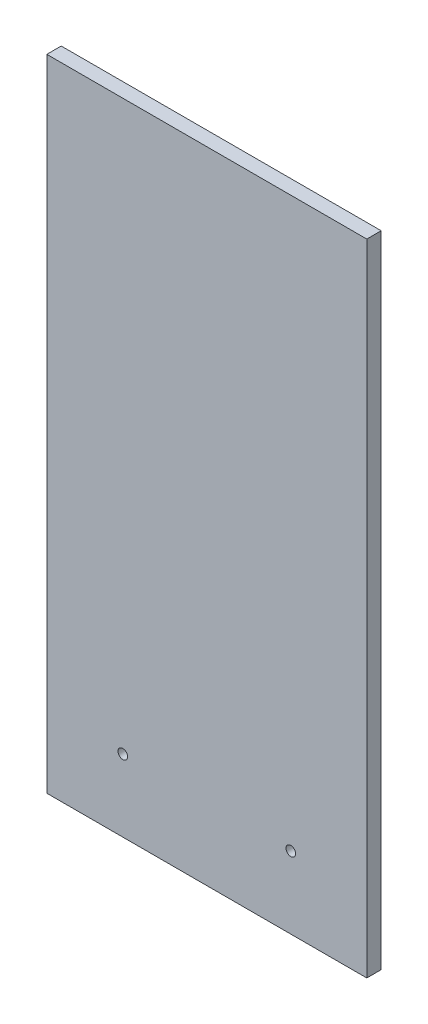
SolidWorks part; units mm, degrees
ref_plane "Plan de face" through (0, 0, 0) normal (0, 0, 1) x (1, 0, 0)
ref_plane "Plan de dessus" through (0, 0, 0) normal (0, 1, 0) x (1, 0, 0)
ref_plane "Plan de droite" through (0, 0, 0) normal (1, 0, 0) x (0, 0, -1)
sketch "Esquisse1" plane through (0, 0, 0) normal (0, 0, 1) x (1, 0, 0)
  line L1 (0, 0) -> (400, 0)
  line L2 (0, 0) -> (0, 800)
  line L3 (0, 800) -> (400, 800)
  line L4 (400, 0) -> (400, 800)
  dimension "D1" = 400
  dimension "D2" = 800
extrude "Boss.-Extru.1" add sketch "Esquisse1" along normal blind 18
sketch "Esquisse2" plane through (0, 0, 18) normal (0, 0, 1) x (1, 0, 0)
  line L0 (200, 0) -> (200, 90) construction
  line L1 (0, 0) -> (400, 0) construction
  line L2 (200, 90) -> (95, 90) construction
  circle A0 centre (95, 90) radius 6
  circle A1 centre (305, 90) radius 6
  dimension "D1" = 12
  dimension "D2" = 210
  dimension "D3" = 90
extrude "Enlèv. mat.-Extru.1" cut sketch "Esquisse2" against normal through all both and the other way through all
